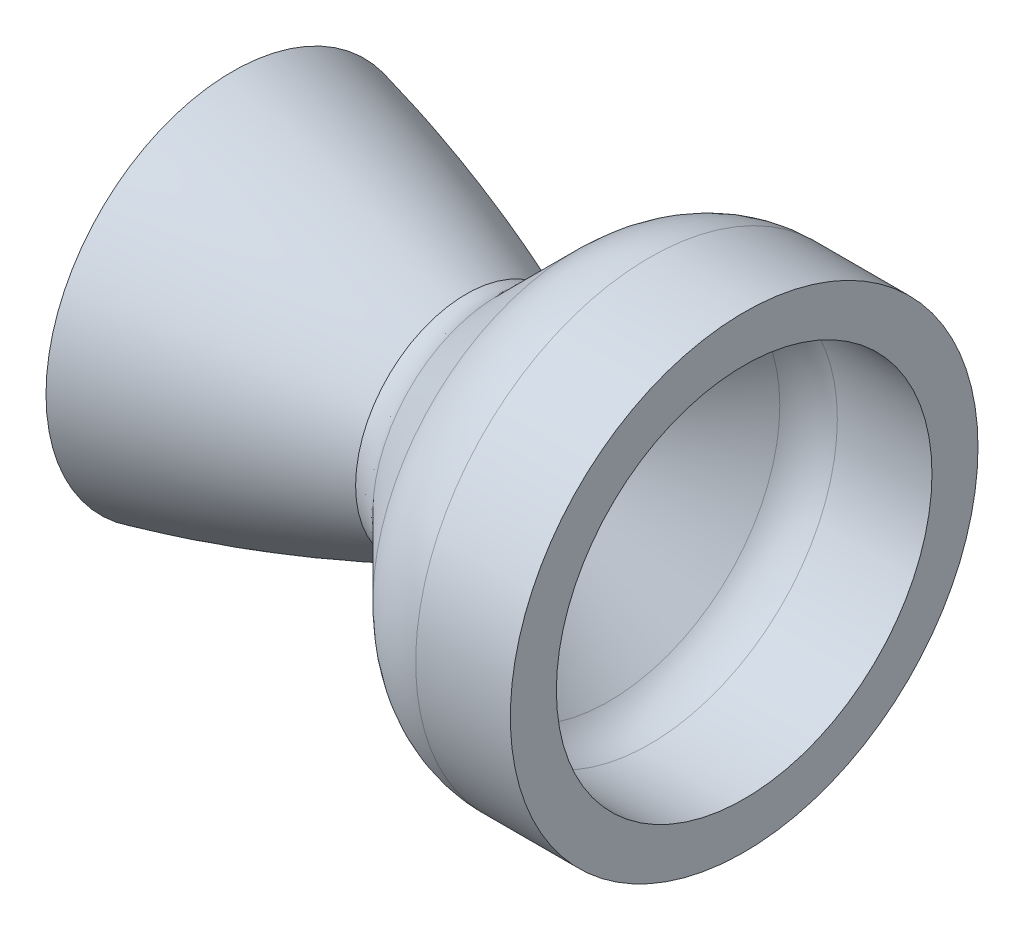
SolidWorks part; units mm, degrees
ref_plane "Front Plane" through (0, 0, 0) normal (0, 0, 1) x (1, 0, 0)
ref_plane "Top Plane" through (0, 0, 0) normal (0, 1, 0) x (1, 0, 0)
ref_plane "Right Plane" through (0, 0, 0) normal (1, 0, 0) x (0, 0, -1)
sketch "Sketch1" plane through (0, 0, 0) normal (0, 0, 1) x (1, 0, 0)
  line L0 (50.6746, 32.6533) -> (34.2162, 32.6533)
  line L1 (27.1452, 29.7244) -> (13.5414, 16.1206)
  line L3 (0, 0) -> (-234.9488, 0) construction
  line L8 (50.6746, 40.6533) -> (34.2162, 40.6533)
  line L12 (21.4883, 35.3813) -> (7.8845, 21.7775)
  line L14 (-40.0966, 24.6298) -> (-38.2841, 32.4218)
  line L16 (50.6746, 32.6533) -> (50.6746, 40.6533)
  arc A0 (34.2162, 32.6533) -> (27.1452, 29.7244) centre (34.2162, 22.6533) ccw
  arc A4 (34.2162, 40.6533) -> (21.4883, 35.3813) centre (34.2162, 22.6533) ccw
  arc A8 (7.8845, 21.7775) -> (2.3477, 19.2268) centre (1.662, 28) cw construction
  arc A10 (0.7687, 11.2238) -> (0, 11.536) centre (12.287, 40.6824) cw construction
  arc A11 (13.5414, 16.1206) -> (0.7687, 11.2238) centre (1.662, 28) cw construction
  arc A12 (13.5414, 16.1206) -> (1.662, 11.2) centre (1.662, 28) cw
  arc A13 (1.662, 11.2) -> (0, 11.536) centre (1.662, 15.4784) cw
  arc A16 (2.3477, 19.2268) -> (2.3477, 19.2268) centre (2.3477, 19.2268) cw construction
  arc A19 (7.8845, 21.7775) -> (2.3477, 19.2268) centre (1.662, 28) cw
  spline S0 degree 2 poles (0, 11.536) (-19.9352, 19.9399) (-40.0966, 24.6298) knots 0 0 0 1 1 1 construction
  spline S1 degree 1 poles (2.3477, 19.2268) (-38.2841, 32.4218) knots 0 0 1 1 construction
  spline S2 degree 2 poles (0, 11.536) (-19.9352, 19.9399) (-40.0966, 24.6298) knots 0 0 0 1 1 1
  spline S3 degree 2 poles (2.3477, 19.2268) (-17.8145, 27.6576) (-38.2841, 32.4218) knots 0.018503 0.018503 0.018503 1 1 1
  dimension "D1" = 10
  dimension "D4" = 16.8
  dimension "D5" = 4.2784
  dimension "D14" = 32.6533
  dimension "D16" = 23.5294
  dimension "D2" = 11.2
  dimension "D6" = 45
  dimension "D7" = 24.6298
  dimension "D3" = 8
revolve "Revolve1" add sketch "Sketch1" angle 360 about L3
equation "\"theta_t\"= 36.9009 - ( 426.271 / ( \"Aet\" + 7.00037 ) ) + ( 10026.8 / ( \"Aet\" + 7.00037 ) ^ 2 ) - ( 175410 / ( \"Aet\" + 7.00037 ) ^ 3 ) + ( ( 1.6742 * ( 10 ^ 6 ) ) / ( \"Aet\" + 7.00037 ) ^ 4 ) - ( ( 6.7643 * ( 10 ^ 6 ) ) / ( \"Aet\" + 7.00037 ) ^ 5 )'Do NOT Change!"
equation "\"rt\"= 11.2'Desired throat radius here"
equation "\"re\"= sqr ( \"rt\" ^ 2 * \"Aet\" )'Do NOT Change!"
equation "\"Aet\"= 4.836'Desired exit area ratio here"
equation "\"L\"= 0.8 * ( ( \"re\" / tan ( 15 ) ) - ( \"rt\" / tan ( 15 ) ) )'Do NOT Change!"
equation "\"lc\"= ( \"l*\" / \"cr\" )'Do NOT Change!"
equation "\"b\"= tan ( \"theta_t\" )'Do NOT Change!"
equation "\"a\"= ( \"re\" - \"b\" * \"L\" - \"c\" ) / \"L\" ^ 2'Do NOT Change!"
equation "\"c\"= \"rt\" * ( 1.382 - 0.382 * cos ( \"theta_t\" ) )'Do NOT Change!"
equation "\"cr\"= 8.5'Desired contraction ratio here"
equation "\"rc\"= sqr ( \"cr\" * ( \"rt\" ^ 2 ) )'Do NOT Change!"
equation "\"D14@Sketch1\"=\"rc\""
equation "\"l*\"= 200'Desired specific length here"
equation "\"D16@Sketch1\"=\"lc\""
equation "\"th\"= 8'Desired wall thickness here"
equation "\"theta_cr\"= 45deg'Desired contraction angle here"
equation "\"theta_e\"= 5.48 + ( 134.316 / ( \"Aet\" + 1.49269 ) ) - ( 1742.02 / ( \"Aet\" + 1.49269 ) ^ 2 ) + ( 13091 / ( \"Aet\" + 1.49269 ) ^ 3 ) - ( 41929.9 / ( \"Aet\" + 1.49269 ) ^ 4 ) + ( 44445.1 / ( \"Aet\" + 1.49269 ) ^ 5 )'Do NOT Change!"
equation "\"Nx\"= 0'Do NOT Change!"
equation "\"Ny\"= \"c\"'Do NOT Change!"
equation "\"Qx\"= ( \"re\" - ( tan ( \"theta_e\" ) * \"L\" ) - \"c\" ) / ( tan ( \"theta_t\" ) - tan ( \"theta_e\" ) )'Do NOT Change!"
equation "\"Qy\"= tan ( \"theta_t\" ) * \"Qx\" + \"c\"'Do NOT Change!"
equation "\"Ex\"= \"L\"'Do NOT Change!"
equation "\"Ey\"= \"re\"'Do NOT Change!"
equation "\"D3@Sketch1\"=\"th\""
equation "\"D2@Sketch1\"=\"rt\""
equation "\"D4@Sketch1\"=\"rt\"*1.5"
equation "\"D5@Sketch1\"=\"rt\"*0.382"
equation "\"D6@Sketch1\"=\"theta_cr\""
equation "\"D7@Sketch1\"=\"re\""
